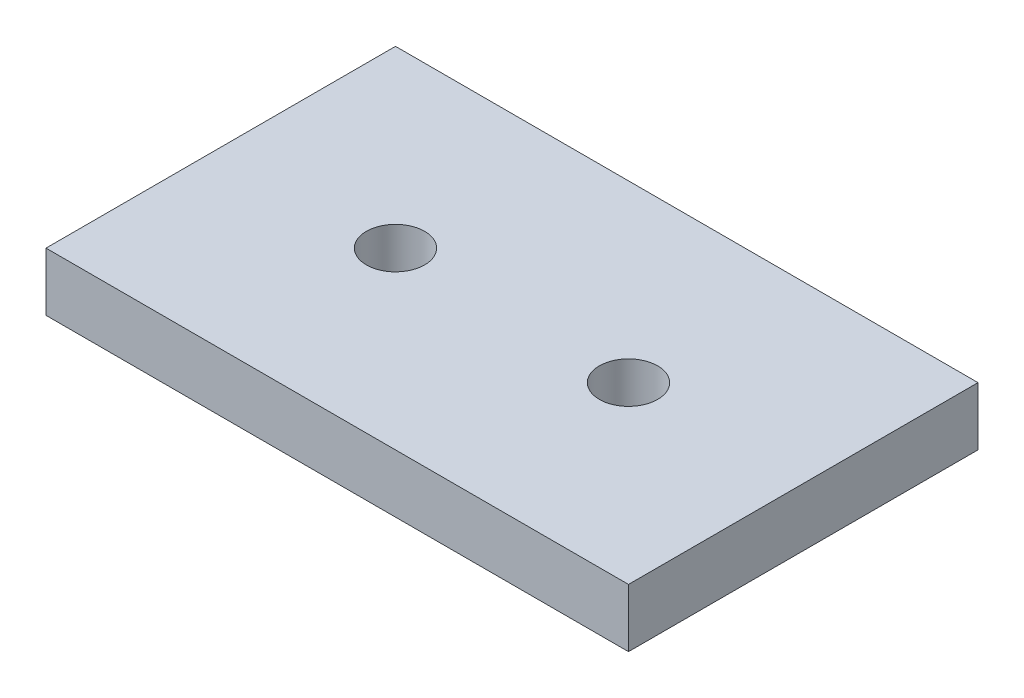
SolidWorks part; units mm, degrees
ref_plane "前视基准面" through (0, 0, 0) normal (0, 0, 1) x (1, 0, 0)
ref_plane "上视基准面" through (0, 0, 0) normal (0, 1, 0) x (1, 0, 0)
ref_plane "右视基准面" through (0, 0, 0) normal (1, 0, 0) x (0, 0, -1)
other "Configuration Table"
sketch "草图1" plane through (0, 0, 0) normal (0, 1, 0) x (1, 0, 0)
  line L1 (-50, -30) -> (50, -30)
  line L2 (-50, -30) -> (-50, 30)
  line L3 (-50, 30) -> (50, 30)
  line L4 (50, -30) -> (50, 30)
  line L5 (-50, -30) -> (50, 30) construction
  line L6 (-50, 30) -> (50, -30) construction
  point P0 (0, 0)
extrude "凸台-拉伸1" add sketch "草图1" along normal blind 10
sketch "草图2" plane through (0, 0, 0) normal (0, 1, 0) x (1, 0, 0)
  circle A0 centre (-20, 0) radius 5
extrude "切除-拉伸1" cut sketch "草图2" along normal blind 20
sketch "草图3" plane through (0, 0, 0) normal (0, 1, 0) x (1, 0, 0)
  circle A0 centre (20, 0) radius 5
extrude "切除-拉伸2" cut sketch "草图3" along normal blind 20
chamfer "倒角1" distance 1 angle 45 2 edges at (20, 0, 5) (-20, 0, 5)
sketch "草图4" plane through (0, 0, 0) normal (0, 1, 0) x (1, 0, 0)
  line L0 (-10, -20) -> (10, -20)
